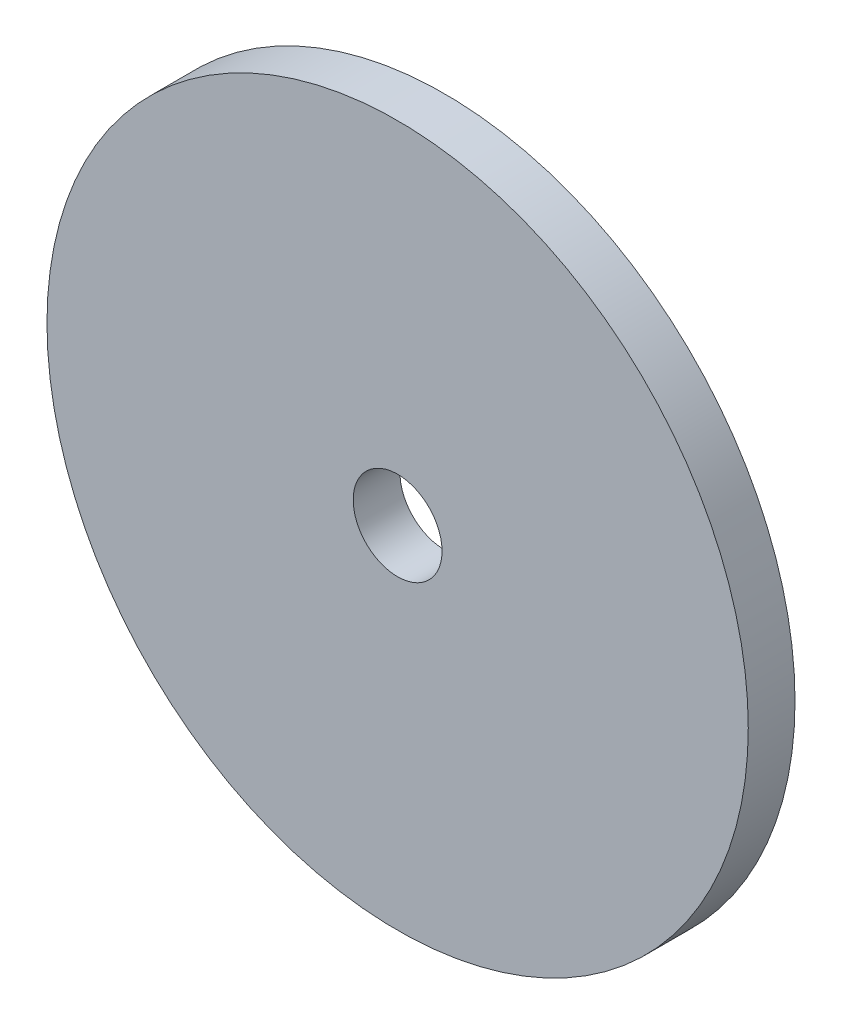
SolidWorks part; units mm, degrees
ref_plane "前视基准面" through (0, 0, 0) normal (0, 0, 1) x (1, 0, 0)
ref_plane "上视基准面" through (0, 0, 0) normal (0, 1, 0) x (1, 0, 0)
ref_plane "右视基准面" through (0, 0, 0) normal (1, 0, 0) x (0, 0, -1)
sketch "草图1" plane through (0, 0, 0) normal (0, 0, 1) x (1, 0, 0)
  circle A0 centre (-17.4661, -11.0469) radius 75
extrude "凸台-拉伸3" add sketch "草图1" along normal blind 10
sketch "草图2" plane through (0, 0, 10) normal (0, 0, 1) x (1, 0, 0)
  circle A0 centre (-17.4661, -11.0469) radius 9.5
extrude "切除-拉伸1" cut sketch "草图2" against normal blind 10
